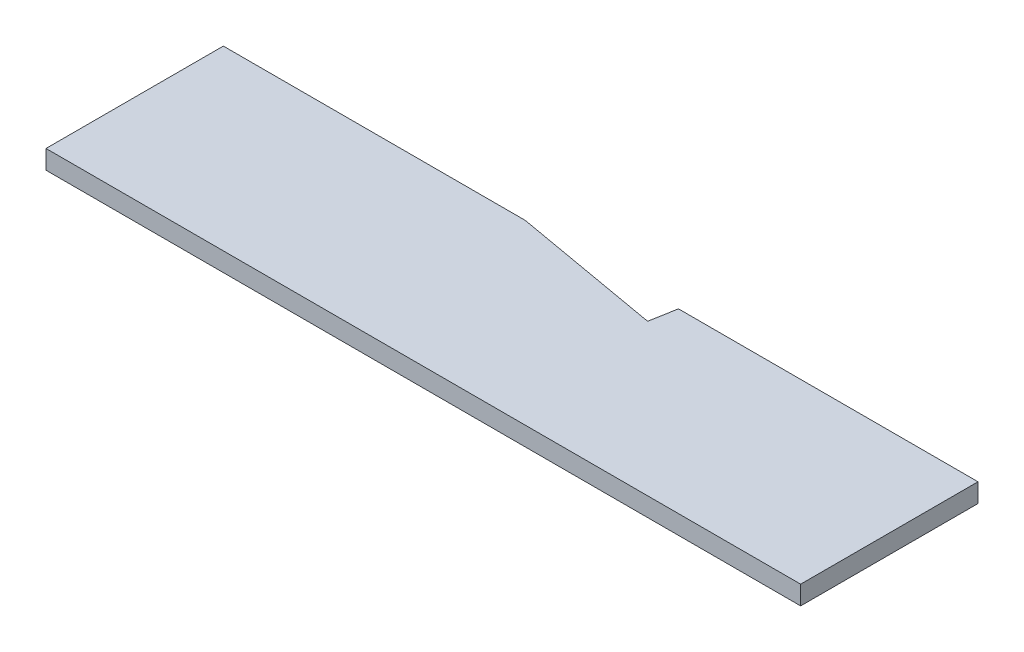
SolidWorks part; units mm, degrees
ref_plane "Front Plane" through (0, 0, 0) normal (0, 0, 1) x (1, 0, 0)
ref_plane "Top Plane" through (0, 0, 0) normal (0, 1, 0) x (1, 0, 0)
ref_plane "Right Plane" through (0, 0, 0) normal (1, 0, 0) x (0, 0, -1)
sketch "Sketch1" plane through (0, 0, 0) normal (0, 1, 0) x (1, 0, 0)
  line L0 (101.6, 59.69) -> (151.6282, 50.8687)
  line L1 (0, 0) -> (254, 0)
  line L2 (0, 0) -> (0, 59.69)
  line L3 (0, 59.69) -> (101.6, 59.69)
  line L4 (254, 0) -> (254, 59.69)
  line L5 (151.6282, 50.8687) -> (153.1837, 59.69)
  line L6 (153.1837, 59.69) -> (254, 59.69)
  dimension "D1" = 254
  dimension "D2" = 59.69
  dimension "D3" = 10
  dimension "D4" = 50.8
  dimension "D5" = 101.6
extrude "Boss-Extrude1" add sketch "Sketch1" along normal blind 6.35
